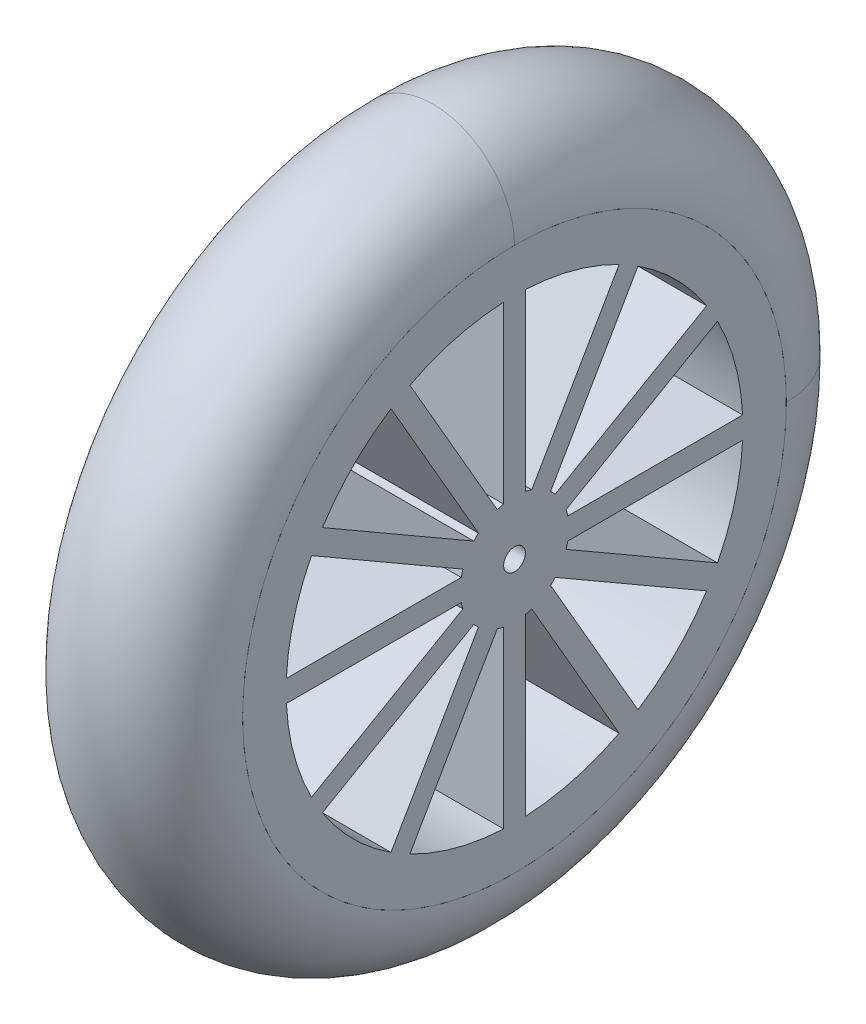
SolidWorks part; units mm, degrees
ref_plane "Front Plane" through (0, 0, 0) normal (0, 0, 1) x (1, 0, 0)
ref_plane "Top Plane" through (0, 0, 0) normal (0, 1, 0) x (1, 0, 0)
ref_plane "Right Plane" through (0, 0, 0) normal (1, 0, 0) x (0, 0, -1)
sketch "Sketch1" plane through (0, 0, 0) normal (1, 0, 0) x (0, 0, -1)
  circle A0 centre (0, 0) radius 1.27
  circle A1 centre (0, 0) radius 31.75
  dimension "D1" = 2.54
  dimension "D2" = 63.5
extrude "Boss-Extrude1" add sketch "Sketch1" along normal blind 19.05
sketch "Sketch2" plane through (19.05, 0, 0) normal (1, 0, 0) x (0, 0, -1)
  line L0 (0, 0) -> (0, 21.0896) construction
  line L1 (-1.27, 6.2217) -> (-1.27, 26.6397)
  line L2 (1.27, 26.6397) -> (1.27, 6.2217)
  line L3 (14.4197, 22.4357) -> (4.2107, 4.7532)
  line L4 (2.011, 6.0232) -> (12.22, 23.7057)
  line L5 (23.7057, 12.22) -> (6.0232, 2.011)
  line L6 (4.7532, 4.2107) -> (22.4357, 14.4197)
  line L7 (26.6397, -1.27) -> (6.2217, -1.27)
  line L8 (6.2217, 1.27) -> (26.6397, 1.27)
  line L9 (22.4357, -14.4197) -> (4.7532, -4.2107)
  line L10 (6.0232, -2.011) -> (23.7057, -12.22)
  line L11 (12.22, -23.7057) -> (2.011, -6.0232)
  line L12 (4.2107, -4.7532) -> (14.4197, -22.4357)
  line L13 (-1.27, -26.6397) -> (-1.27, -6.2217)
  line L14 (1.27, -6.2217) -> (1.27, -26.6397)
  line L15 (-14.4197, -22.4357) -> (-4.2107, -4.7532)
  line L16 (-2.011, -6.0232) -> (-12.22, -23.7057)
  line L17 (-23.7057, -12.22) -> (-6.0232, -2.011)
  line L18 (-4.7532, -4.2107) -> (-22.4357, -14.4197)
  line L19 (-26.6397, 1.27) -> (-6.2217, 1.27)
  line L20 (-6.2217, -1.27) -> (-26.6397, -1.27)
  line L21 (-22.4357, 14.4197) -> (-4.7532, 4.2107)
  line L22 (-6.0232, 2.011) -> (-23.7057, 12.22)
  line L23 (-12.22, 23.7057) -> (-2.011, 6.0232)
  line L24 (-4.2107, 4.7532) -> (-14.4197, 22.4357)
  arc A0 (12.22, 23.7057) -> (1.27, 26.6397) centre (0, 0) ccw
  arc A1 (2.011, 6.0232) -> (1.27, 6.2217) centre (0, 0) ccw
  circle A2 centre (0, 0) radius 26.67
  arc A3 (-1.27, 26.6397) -> (-12.22, 23.7057) centre (0, 0) ccw
  arc A4 (4.7532, 4.2107) -> (4.2107, 4.7532) centre (0, 0) ccw
  circle A5 centre (0, 0) radius 6.35
  arc A6 (-1.27, 6.2217) -> (-2.011, 6.0232) centre (0, 0) ccw
  arc A7 (22.4357, 14.4197) -> (14.4197, 22.4357) centre (0, 0) ccw
  arc A8 (26.6397, 1.27) -> (23.7057, 12.22) centre (0, 0) ccw
  arc A9 (6.2217, 1.27) -> (6.0232, 2.011) centre (0, 0) ccw
  arc A10 (23.7057, -12.22) -> (26.6397, -1.27) centre (0, 0) ccw
  arc A11 (6.0232, -2.011) -> (6.2217, -1.27) centre (0, 0) ccw
  arc A12 (4.2107, -4.7532) -> (4.7532, -4.2107) centre (0, 0) ccw
  arc A13 (1.27, -6.2217) -> (2.011, -6.0232) centre (0, 0) ccw
  arc A14 (-4.7532, -4.2107) -> (-4.2107, -4.7532) centre (0, 0) ccw
  arc A15 (-6.2217, -1.27) -> (-6.0232, -2.011) centre (0, 0) ccw
  arc A16 (-6.0232, 2.011) -> (-6.2217, 1.27) centre (0, 0) ccw
  arc A17 (-4.2107, 4.7532) -> (-4.7532, 4.2107) centre (0, 0) ccw
  arc A18 (-14.4197, 22.4357) -> (-22.4357, 14.4197) centre (0, 0) ccw
  arc A19 (-23.7057, 12.22) -> (-26.6397, 1.27) centre (0, 0) ccw
  arc A20 (-26.6397, -1.27) -> (-23.7057, -12.22) centre (0, 0) ccw
  arc A21 (-22.4357, -14.4197) -> (-14.4197, -22.4357) centre (0, 0) ccw
  arc A22 (-12.22, -23.7057) -> (-1.27, -26.6397) centre (0, 0) ccw
  arc A23 (1.27, -26.6397) -> (12.22, -23.7057) centre (0, 0) ccw
  arc A24 (14.4197, -22.4357) -> (22.4357, -14.4197) centre (0, 0) ccw
  arc A25 (-2.011, -6.0232) -> (-1.27, -6.2217) centre (0, 0) ccw
  point P13 (0, 0)
  point P58 (0, 0)
  dimension "D3" = 2.54
  dimension "D1" = 5.08
  dimension "D2" = 5.08
  dimension "D4" = 12
extrude "Cut-Extrude1" cut sketch "Sketch2" against normal through all both and the other way through all
sketch "Sketch3" plane through (0, 0, 0) normal (0, 0, 1) x (1, 0, 0)
  line L0 (19.05, 31.75) -> (0, 31.75) construction
  line L1 (19.05, 31.75) -> (0, 31.75)
  arc A0 (0, 31.75) -> (19.05, 31.75) centre (9.525, 31.75) cw
sweep "Sweep1" add profiles "Sketch3" path edge at (19.05, 0, -31.75)
